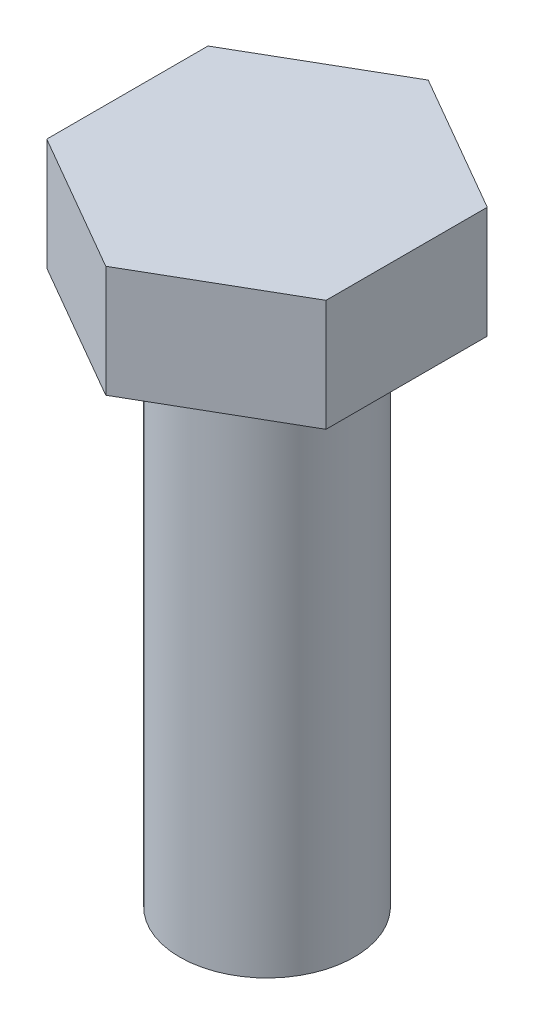
SolidWorks part; units mm, degrees
material "Plain Carbon Steel"
ref_plane "Front Plane" through (0, 0, 0) normal (0, 0, 1) x (1, 0, 0)
ref_plane "Top Plane" through (0, 0, 0) normal (0, 1, 0) x (1, 0, 0)
ref_plane "Right Plane" through (0, 0, 0) normal (1, 0, 0) x (0, 0, -1)
sketch "Sketch1" plane through (0, 0, 0) normal (0, 1, 0) x (1, 0, 0)
  line L1 (0, 9.2376) -> (-8, 4.6188)
  line L2 (-8, 4.6188) -> (-8, -4.6188)
  line L3 (-8, -4.6188) -> (0, -9.2376)
  line L4 (0, -9.2376) -> (8, -4.6188)
  line L5 (8, -4.6188) -> (8, 4.6188)
  line L6 (8, 4.6188) -> (0, 9.2376)
  circle A0 centre (0, 0) radius 8 construction
extrude "Boss-Extrude1" add sketch "Sketch1" along normal blind 6.4
sketch "Sketch2" plane through (0, 0, 0) normal (0, 1, 0) x (1, 0, 0)
  circle A0 centre (0, 0) radius 5
extrude "Boss-Extrude2" add sketch "Sketch2" against normal blind 30
